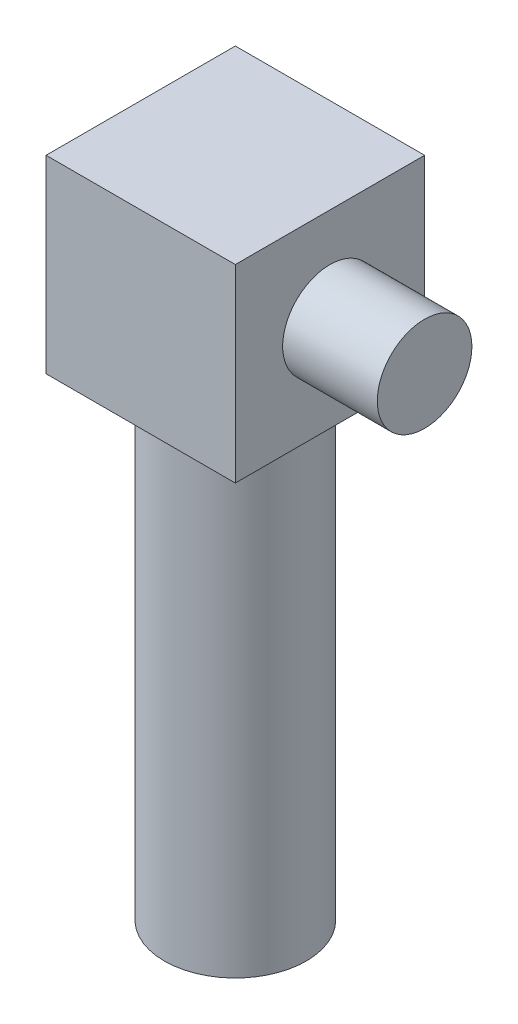
SolidWorks part; units mm, degrees
ref_plane "Front Plane" through (0, 0, 0) normal (0, 0, 1) x (1, 0, 0)
ref_plane "Top Plane" through (0, 0, 0) normal (0, 1, 0) x (1, 0, 0)
ref_plane "Right Plane" through (0, 0, 0) normal (1, 0, 0) x (0, 0, -1)
sketch "Sketch1" plane through (0, 0, 0) normal (0, 1, 0) x (1, 0, 0)
  circle A0 centre (0, 0) radius 5
  circle A1 centre (0, 0) radius 7.5
  dimension "D1" = 10
  dimension "D2" = 15
extrude "Boss-Extrude1" add sketch "Sketch1" along normal blind 50 contours A1 A0
sketch "Sketch3" plane through (0, 50, 0) normal (0, 1, 0) x (1, 0, 0)
  line L1 (-10, -10) -> (10, -10)
  line L2 (-10, -10) -> (-10, 10)
  line L3 (-10, 10) -> (10, 10)
  line L4 (10, -10) -> (10, 10)
  line L5 (-10, -10) -> (10, 10) construction
  line L6 (-10, 10) -> (10, -10) construction
  point P0 (0, 0)
  circle M3 centre (0, 0) radius 5
  circle M4 centre (0, 0) radius 7.5
  dimension "D1" = 20
  dimension "D2" = 20
extrude "Boss-Extrude2" add sketch "Sketch3" along normal blind 20 contours L1 L4 L3 L2 M4 | M4 M3 | M3
sketch "Sketch4" plane through (10, 0, 0) normal (1, 0, 0) x (0, 0, -1)
  line L0 (-10, 70) -> (10, 70) construction
  line L1 (-10, 70) -> (-10, 50) construction
  circle A0 centre (0, 60) radius 5
  point P2 (0, 0)
  point P5 (0, 70)
  point P8 (-10, 60)
  dimension "D1" = 10
extrude "Boss-Extrude3" add sketch "Sketch4" along normal blind 10 contours A0
